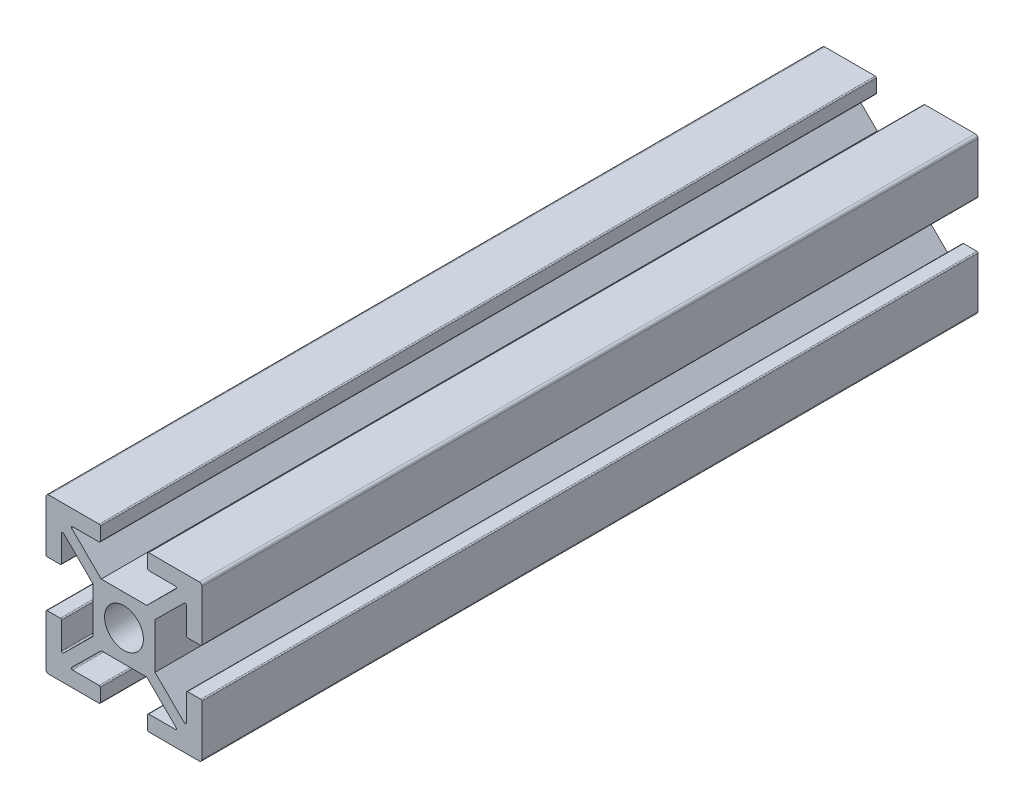
SolidWorks part; units mm, degrees
ref_plane "Front Plane" through (0, 0, 0) normal (0, 0, 1) x (1, 0, 0)
ref_plane "Top Plane" through (0, 0, 0) normal (0, 1, 0) x (1, 0, 0)
ref_plane "Right Plane" through (0, 0, 0) normal (1, 0, 0) x (0, 0, -1)
sketch "Sketch1" plane through (0, 0, 0) normal (0, 0, 1) x (1, 0, 0)
  line L0 (-7.4274, 2.1557) -> (-5.7274, 2.1557)
  line L1 (-0.7274, 9.1557) -> (-7.2274, 9.1557)
  line L2 (-7.5774, 2.3057) -> (-7.5774, 8.8057)
  line L3 (5.4021, 3.1557) -> (-0.4643, 3.1557)
  line L4 (-1.5311, -3.7897) -> (-1.5311, 2.1011)
  line L5 (-5.5774, 2.3057) -> (-5.5774, 5.7419)
  line L6 (-4.1455, 7.1557) -> (-0.7274, 7.1557)
  line L7 (-0.5774, 7.3057) -> (-0.5774, 9.0057)
  line L8 (-5.5774, 7.1557) -> (-1.5311, 3.1557) construction
  line L9 (-5.3219, 5.8486) -> (-1.5311, 2.1011)
  line L10 (-4.2509, 6.899) -> (-0.4643, 3.1557)
  line L11 (10.5152, 7.1557) -> (6.4689, 3.1557) construction
  line L12 (2.4689, -0.8443) -> (2.4689, 10.8443) construction
  line L13 (2.4689, -0.8443) -> (-12.5152, -0.8443) construction
  line L14 (9.1887, 6.899) -> (5.4021, 3.1557)
  line L15 (10.2598, 5.8486) -> (6.4689, 2.1011)
  line L16 (5.5152, 7.3057) -> (5.5152, 9.0057)
  line L17 (9.0833, 7.1557) -> (5.6652, 7.1557)
  line L18 (10.5152, 2.3057) -> (10.5152, 5.7419)
  line L19 (6.4689, -3.7897) -> (6.4689, 2.1011)
  line L20 (12.5152, 2.3057) -> (12.5152, 8.8057)
  line L21 (5.6652, 9.1557) -> (12.1652, 9.1557)
  line L22 (12.3652, 2.1557) -> (10.6652, 2.1557)
  line L23 (10.5152, -8.8443) -> (6.4689, -4.8443) construction
  line L24 (-5.5774, -8.8443) -> (-1.5311, -4.8443) construction
  line L25 (12.3652, -3.8443) -> (10.6652, -3.8443)
  line L26 (5.6652, -10.8443) -> (12.1652, -10.8443)
  line L27 (12.5152, -3.9943) -> (12.5152, -10.4943)
  line L28 (10.5152, -3.9943) -> (10.5152, -7.4305)
  line L29 (9.0833, -8.8443) -> (5.6652, -8.8443)
  line L30 (5.5152, -8.9943) -> (5.5152, -10.6943)
  line L31 (10.2598, -7.5372) -> (6.4689, -3.7897)
  line L32 (9.1887, -8.5876) -> (5.4021, -4.8443)
  line L33 (-4.2509, -8.5876) -> (-0.4643, -4.8443)
  line L34 (-5.3219, -7.5372) -> (-1.5311, -3.7897)
  line L35 (-0.5774, -8.9943) -> (-0.5774, -10.6943)
  line L36 (-4.1455, -8.8443) -> (-0.7274, -8.8443)
  line L37 (-5.5774, -3.9943) -> (-5.5774, -7.4305)
  line L38 (5.4021, -4.8443) -> (-0.4643, -4.8443)
  line L39 (-7.5774, -3.9943) -> (-7.5774, -10.4943)
  line L40 (-0.7274, -10.8443) -> (-7.2274, -10.8443)
  line L41 (-7.4274, -3.8443) -> (-5.7274, -3.8443)
  circle A0 centre (2.4689, -0.8443) radius 2.5
  arc A1 (-7.5774, 8.8057) -> (-7.2274, 9.1557) centre (-7.2274, 8.8057) cw
  arc A2 (-7.4274, 2.1557) -> (-7.5774, 2.3057) centre (-7.4274, 2.3057) cw
  arc A3 (-5.7274, 2.1557) -> (-5.5774, 2.3057) centre (-5.7274, 2.3057) ccw
  arc A4 (-0.7274, 9.1557) -> (-0.5774, 9.0057) centre (-0.7274, 9.0057) cw
  arc A5 (-0.7274, 7.1557) -> (-0.5774, 7.3057) centre (-0.7274, 7.3057) ccw
  arc A6 (-4.2509, 6.899) -> (-4.1455, 7.1557) centre (-4.1455, 7.0057) cw
  arc A7 (-5.3219, 5.8486) -> (-5.5774, 5.7419) centre (-5.4274, 5.7419) ccw
  arc A8 (10.2598, 5.8486) -> (10.5152, 5.7419) centre (10.3652, 5.7419) cw
  arc A9 (9.1887, 6.899) -> (9.0833, 7.1557) centre (9.0833, 7.0057) ccw
  arc A10 (5.6652, 7.1557) -> (5.5152, 7.3057) centre (5.6652, 7.3057) cw
  arc A11 (5.6652, 9.1557) -> (5.5152, 9.0057) centre (5.6652, 9.0057) ccw
  arc A12 (10.6652, 2.1557) -> (10.5152, 2.3057) centre (10.6652, 2.3057) cw
  arc A13 (12.3652, 2.1557) -> (12.5152, 2.3057) centre (12.3652, 2.3057) ccw
  arc A14 (12.5152, 8.8057) -> (12.1652, 9.1557) centre (12.1652, 8.8057) ccw
  arc A15 (12.5152, -10.4943) -> (12.1652, -10.8443) centre (12.1652, -10.4943) cw
  arc A16 (12.3652, -3.8443) -> (12.5152, -3.9943) centre (12.3652, -3.9943) cw
  arc A17 (10.6652, -3.8443) -> (10.5152, -3.9943) centre (10.6652, -3.9943) ccw
  arc A18 (5.6652, -10.8443) -> (5.5152, -10.6943) centre (5.6652, -10.6943) cw
  arc A19 (5.6652, -8.8443) -> (5.5152, -8.9943) centre (5.6652, -8.9943) ccw
  arc A20 (9.1887, -8.5876) -> (9.0833, -8.8443) centre (9.0833, -8.6943) cw
  arc A21 (10.2598, -7.5372) -> (10.5152, -7.4305) centre (10.3652, -7.4305) ccw
  arc A22 (-5.3219, -7.5372) -> (-5.5774, -7.4305) centre (-5.4274, -7.4305) cw
  arc A23 (-4.2509, -8.5876) -> (-4.1455, -8.8443) centre (-4.1455, -8.6943) ccw
  arc A24 (-0.7274, -8.8443) -> (-0.5774, -8.9943) centre (-0.7274, -8.9943) cw
  arc A25 (-0.7274, -10.8443) -> (-0.5774, -10.6943) centre (-0.7274, -10.6943) ccw
  arc A26 (-5.7274, -3.8443) -> (-5.5774, -3.9943) centre (-5.7274, -3.9943) cw
  arc A27 (-7.4274, -3.8443) -> (-7.5774, -3.9943) centre (-7.4274, -3.9943) ccw
  arc A28 (-7.5774, -10.4943) -> (-7.2274, -10.8443) centre (-7.2274, -10.4943) ccw
  point P27 (5.5152, 7.1557)
  point P28 (12.5152, -10.8443)
  point P47 (6.4689, -0.8443)
  point P57 (2.4689, 3.1557)
  point P59 (5.5152, 9.1557)
  point P60 (10.5152, 2.1557)
  point P61 (12.5152, 2.1557)
  point P62 (12.5152, 9.1557)
  point P112 (-1.5311, -0.8443)
  point P113 (12.5152, -3.8443)
  point P114 (10.5152, -3.8443)
  point P115 (5.5152, -10.8443)
  point P116 (2.4689, -4.8443)
  point P117 (-0.5774, -8.8443)
  point P118 (-0.5774, -10.8443)
  point P119 (-5.5774, -3.8443)
  point P120 (5.5152, -8.8443)
  point P121 (-7.5774, -3.8443)
  point P122 (-7.5774, -10.8443)
  dimension "D3" = 0.35
  dimension "D4" = 0.15
  dimension "D5" = 0.15
  dimension "D6" = 0.15
  dimension "D7" = 0.15
  dimension "D8" = 0.15
  dimension "D9" = 0.15
  dimension "D1" = 0.75
  dimension "D2" = 0.75
extrude "Boss-Extrude1" add sketch "Sketch1" along normal blind 100
